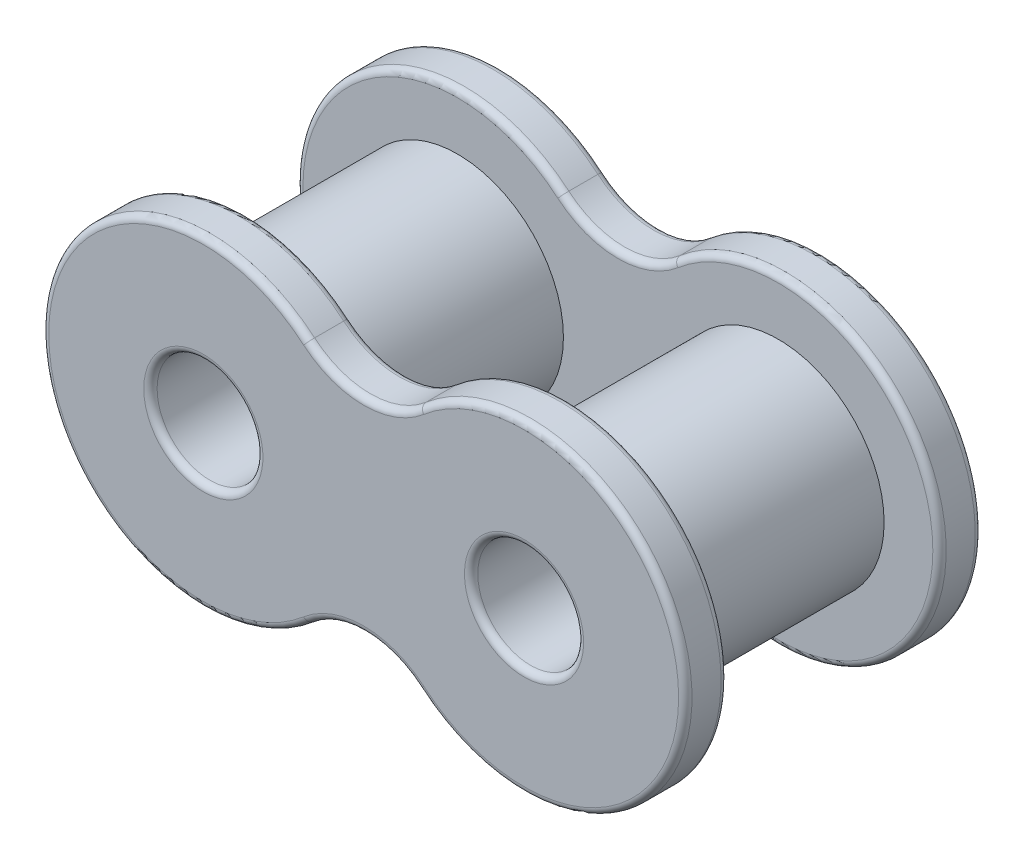
SolidWorks part; units mm, degrees
ref_plane "Front Plane" through (0, 0, 0) normal (0, 0, 1) x (1, 0, 0)
ref_plane "Top Plane" through (0, 0, 0) normal (0, 1, 0) x (1, 0, 0)
ref_plane "Right Plane" through (0, 0, 0) normal (1, 0, 0) x (0, 0, -1)
sketch "Sketch1" plane through (0, 0, 0) normal (0, 0, 1) x (1, 0, 0)
  line L0 (0, 5.1022) -> (0, 0) construction
  line L1 (0, 0) -> (-6, 0) construction
  arc A0 (-2.085, 4.5928) -> (-2.085, -4.5928) centre (-6, 0) ccw
  circle A1 centre (-6, 0) radius 1.98
  circle A2 centre (6, 0) radius 1.98
  arc A3 (2.085, 4.5928) -> (2.085, -4.5928) centre (6, 0) cw
  arc A4 (-2.085, 4.5928) -> (2.085, 4.5928) centre (0, 7.0389) ccw
  arc A5 (-2.085, -4.5928) -> (2.085, -4.5928) centre (0, -7.0389) cw
  dimension "D1" = 12.07
  dimension "D2" = 3.96
  dimension "D4" = 3.2141
  dimension "D3" = 6
extrude "Boss-Extrude1" add sketch "Sketch1" along normal blind 1.587
fillet "Fillet1" radius 0.25 8 edges at (0, 3.8248, 1.587) (12.035, 0, 1.587) (0, -3.8248, 1.587) (0, 3.8248, 0) (12.035, 0, 0) (0, -3.8248, 0) (-12.035, 0, 1.587) (-12.035, 0, 0)
sketch "Sketch2" plane through (0, 0, 1.587) normal (0, 0, 1) x (1, 0, 0)
  circle A0 centre (-6, 0) radius 3.962
  circle A1 centre (-6, 0) radius 1.98 construction
  circle A2 centre (-6, 0) radius 1.98
  dimension "D1" = 7.924
extrude "Boss-Extrude2" add sketch "Sketch2" along normal blind 7.9248
mirror "Mirror1" about plane through (0, 0, 0) normal (1, 0, 0) of "Boss-Extrude2"
ref_plane "Plane1" through (0, 0, 5.5494) normal (0, 0, 1) x (1, 0, 0)
mirror "Mirror3" about plane through (0, 0, 5.5494) normal (0, 0, 1) of "Fillet1", "Boss-Extrude1"
fillet "Fillet2" radius 0.25 4 edges at (4.02, 0, 11.0988) (-4.02, 0, 11.0988) (4.02, 0, 0) (-4.02, 0, 0)
